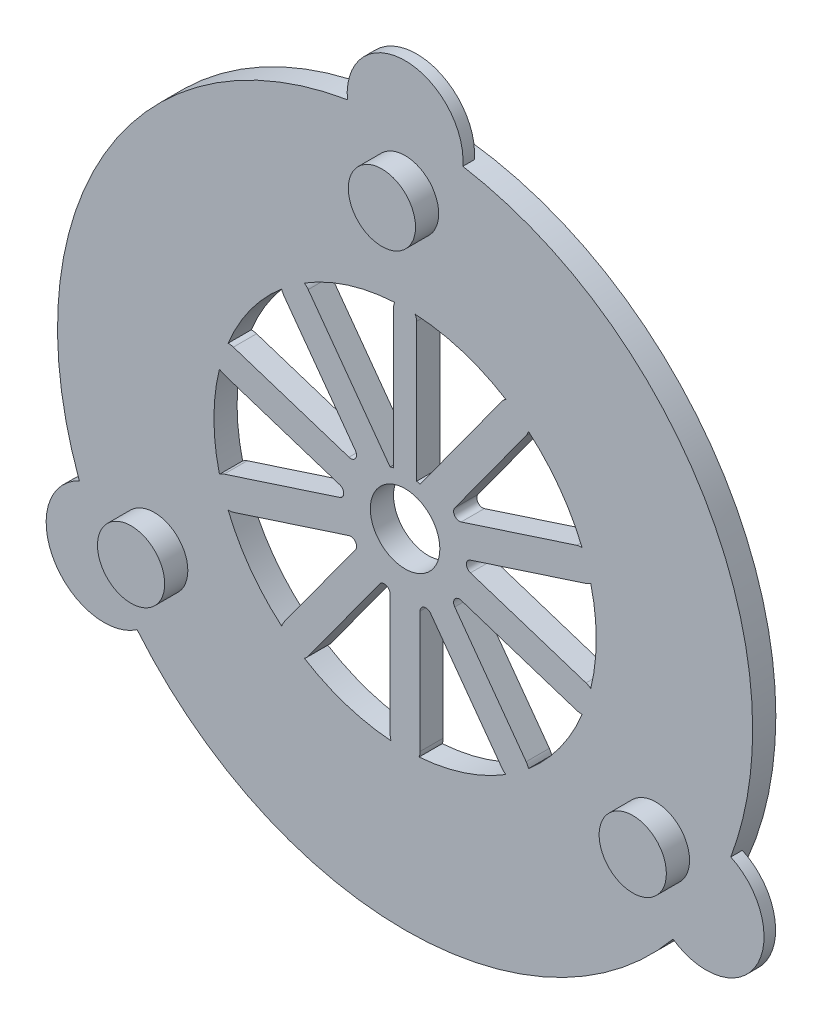
SolidWorks part; units mm, degrees
ref_plane "Спереди" through (0, 0, 0) normal (0, 0, 1) x (1, 0, 0)
ref_plane "Сверху" through (0, 0, 0) normal (0, 1, 0) x (1, 0, 0)
ref_plane "Справа" through (0, 0, 0) normal (1, 0, 0) x (0, 0, -1)
sketch "Sketch1" plane through (0, 0, 0) normal (0, 0, 1) x (1, 0, 0)
  line L0 (3.9, 6.755) -> (7.8, 0) construction
  line L2 (5.85, 10.1325) -> (11.7, 0) construction
  line L4 (7.8, 13.51) -> (15.6, 0) construction
  circle A61 centre (0, 0) radius 20
  circle A131 centre (0, 0) radius 1.25
  circle A484 centre (3.9, 0) radius 1.25
  circle A485 centre (7.8, 0) radius 1.25
  circle A486 centre (11.7, 0) radius 1.25
  circle A487 centre (15.6, 0) radius 1.25
  circle A488 centre (1.95, -3.3775) radius 1.25
  circle A489 centre (3.9, -6.755) radius 1.25
  circle A490 centre (5.85, -10.1325) radius 1.25
  circle A491 centre (7.8, -13.51) radius 1.25
  circle A492 centre (-1.95, -3.3775) radius 1.25
  circle A493 centre (-3.9, -6.755) radius 1.25
  circle A494 centre (-5.85, -10.1325) radius 1.25
  circle A495 centre (-7.8, -13.51) radius 1.25
  circle A496 centre (-3.9, 0) radius 1.25
  circle A497 centre (-7.8, 0) radius 1.25
  circle A498 centre (-11.7, 0) radius 1.25
  circle A499 centre (-15.6, 0) radius 1.25
  circle A500 centre (-1.95, 3.3775) radius 1.25
  circle A501 centre (-3.9, 6.755) radius 1.25
  circle A502 centre (-5.85, 10.1325) radius 1.25
  circle A503 centre (-7.8, 13.51) radius 1.25
  circle A504 centre (1.95, 3.3775) radius 1.25
  circle A505 centre (3.9, 6.755) radius 1.25
  circle A506 centre (5.85, 10.1325) radius 1.25
  circle A507 centre (7.8, 13.51) radius 1.25
  circle A508 centre (5.85, 3.3775) radius 1.25
  circle A509 centre (7.8, 6.755) radius 1.25
  circle A510 centre (9.75, 3.3775) radius 1.25
  circle A511 centre (11.7, 6.755) radius 1.25
  circle A512 centre (9.7491, 10.1341) radius 1.25
  circle A513 centre (13.6509, 3.3759) radius 1.25
  circle A514 centre (5.85, -3.3791) radius 1.25
  circle A515 centre (9.75, -3.3791) radius 1.25
  circle A516 centre (7.8, -6.7566) radius 1.25
  circle A517 centre (11.7, -6.7566) radius 1.25
  circle A518 centre (9.7491, -10.1356) radius 1.25
  circle A519 centre (13.6509, -3.3775) radius 1.25
  circle A520 centre (-0.0013, -6.7573) radius 1.25
  circle A521 centre (1.9487, -10.1348) radius 1.25
  circle A522 centre (-1.9513, -10.1348) radius 1.25
  circle A523 centre (-0.0013, -13.5123) radius 1.25
  circle A524 centre (-3.9032, -13.5123) radius 1.25
  circle A525 centre (3.9005, -13.5123) radius 1.25
  circle A526 centre (-5.8527, -3.3791) radius 1.25
  circle A527 centre (-7.8027, -6.7566) radius 1.25
  circle A528 centre (-9.7527, -3.3791) radius 1.25
  circle A529 centre (-11.7027, -6.7566) radius 1.25
  circle A530 centre (-13.6536, -3.3775) radius 1.25
  circle A531 centre (-9.7518, -10.1356) radius 1.25
  circle A532 centre (-5.8527, 3.3775) radius 1.25
  circle A533 centre (-9.7527, 3.3775) radius 1.25
  circle A534 centre (-7.8027, 6.755) radius 1.25
  circle A535 centre (-11.7027, 6.755) radius 1.25
  circle A536 centre (-9.7518, 10.1341) radius 1.25
  circle A537 centre (-13.6536, 3.3759) radius 1.25
  circle A538 centre (-0.0014, 6.7558) radius 1.25
  circle A539 centre (-1.9514, 10.1333) radius 1.25
  circle A540 centre (1.9486, 10.1333) radius 1.25
  circle A541 centre (-0.0014, 13.5108) radius 1.25
  circle A542 centre (3.9005, 13.5108) radius 1.25
  circle A543 centre (-3.9032, 13.5108) radius 1.25
  circle A544 centre (13.65, -1.1258) radius 2.2517 construction
  circle A545 centre (11.7009, -4.5044) radius 2.2522 construction
  circle A546 centre (9.75, -7.8834) radius 2.2522 construction
  circle A547 centre (7.7987, -11.2591) radius 2.2509 construction
  circle A548 centre (13.65, -1.1258) radius 0.65
  circle A549 centre (11.7009, -4.5044) radius 0.65
  circle A550 centre (9.75, -7.8834) radius 0.65
  circle A551 centre (7.7987, -11.2591) radius 0.65
  circle A552 centre (9.75, -1.1258) radius 0.65
  circle A553 centre (7.8009, -4.5044) radius 0.65
  circle A554 centre (5.85, -7.8834) radius 0.65
  circle A555 centre (3.8987, -11.2591) radius 0.65
  circle A556 centre (5.85, -1.1258) radius 0.65
  circle A557 centre (3.9009, -4.5044) radius 0.65
  circle A558 centre (1.95, -7.8834) radius 0.65
  circle A559 centre (-0.0013, -11.2591) radius 0.65
  circle A560 centre (1.95, -1.1258) radius 0.65
  circle A561 centre (0.0009, -4.5044) radius 0.65
  circle A562 centre (-1.95, -7.8834) radius 0.65
  circle A563 centre (-3.9013, -11.2591) radius 0.65
  circle A564 centre (-1.95, -1.1258) radius 0.65
  circle A565 centre (-3.8991, -4.5044) radius 0.65
  circle A566 centre (-5.85, -7.8834) radius 0.65
  circle A567 centre (-7.8013, -11.2591) radius 0.65
  circle A568 centre (-5.85, -1.1258) radius 0.65
  circle A569 centre (-7.7991, -4.5044) radius 0.65
  circle A570 centre (-9.75, -7.8834) radius 0.65
  circle A572 centre (-9.75, -1.1258) radius 0.65
  circle A573 centre (-11.6991, -4.5044) radius 0.65
  circle A576 centre (-13.65, -1.1258) radius 0.65
  circle A587 centre (0, 2.2517) radius 2.2517 construction
  circle A588 centre (0, 2.2517) radius 0.65
  circle A589 centre (3.9, 2.2517) radius 0.65
  circle A590 centre (7.8, 2.2517) radius 0.65
  circle A591 centre (11.7, 2.2517) radius 0.65
  circle A592 centre (15.6, 2.2517) radius 0.65
  circle A593 centre (1.9491, 5.6297) radius 2.2522 construction
  circle A594 centre (1.9491, 5.6297) radius 0.65
  circle A595 centre (5.8491, 5.6297) radius 0.65
  circle A596 centre (9.7491, 5.6297) radius 0.65
  circle A597 centre (13.6491, 5.6297) radius 0.65
  circle A598 centre (3.8991, 9.0072) radius 2.2522 construction
  circle A599 centre (3.8991, 9.0072) radius 0.65
  circle A600 centre (7.7991, 9.0072) radius 0.65
  circle A601 centre (11.6991, 9.0072) radius 0.65
  circle A602 centre (5.85, 12.3842) radius 2.2517 construction
  circle A603 centre (5.85, 12.3842) radius 0.65
  circle A604 centre (9.75, 12.3842) radius 0.65
  circle A605 centre (5.85, -14.6358) radius 0.65
  circle A606 centre (1.9509, -14.6353) radius 0.65
  circle A607 centre (-1.9491, -14.6353) radius 0.65
  circle A608 centre (-5.85, -14.6358) radius 0.65
  circle A609 centre (-15.6, 2.2517) radius 0.65
  circle A610 centre (-13.65, 5.6281) radius 0.65
  circle A611 centre (-11.7, 9.0056) radius 0.65
  circle A612 centre (-9.75, 12.3842) radius 0.65
  circle A613 centre (-5.85, 12.3842) radius 0.65
  circle A614 centre (-1.95, 12.3842) radius 0.65
  circle A615 centre (1.95, 12.3842) radius 0.65
  circle A616 centre (-7.8, 9.0056) radius 0.65
  circle A617 centre (-9.75, 5.6281) radius 0.65
  circle A618 centre (-11.7, 2.2517) radius 0.65
  circle A619 centre (-3.9, 9.0056) radius 0.65
  circle A620 centre (-5.85, 5.6281) radius 0.65
  circle A621 centre (-7.8, 2.2517) radius 0.65
  circle A622 centre (0, 9.0056) radius 0.65
  circle A623 centre (-1.95, 5.6281) radius 0.65
  circle A624 centre (-3.9, 2.2517) radius 0.65
  circle A625 centre (-15.5991, -4.5044) radius 0.65
  circle A626 centre (-13.65, -7.8834) radius 0.65
  circle A627 centre (-17.55, -7.8834) radius 0.65
  circle A628 centre (-19.5013, -11.2591) radius 0.65
  circle A629 centre (-15.6013, -11.2591) radius 0.65
  circle A630 centre (-11.7013, -11.2591) radius 0.65
  point P51 (0, 0)
  point P125 (-0.0013, -0.0008)
  point P231 (0, 0)
  dimension "D1" = 5
  dimension "D3" = 6
  dimension "D5" = 8
  dimension "D7" = 4
  dimension "D11" = 4
  dimension "D2" = 6
  dimension "D6" = 5
  dimension "D8" = 3
  dimension "D9" = 2
  dimension "D4" = 1.3
  dimension "D10" = 3
ref_plane "Plane1" through (0, 0, 10) normal (0, 0, 1) x (1, 0, 0)
sketch "Sketch2" plane through (0, 0, 10) normal (0, 0, 1) x (1, 0, 0)
  line L0 (-0.0032, 16) -> (0, 0) construction
  line L1 (0.9968, 16.0002) -> (1, 0.0002)
  line L2 (-1.0032, 15.9998) -> (-1, -0.0002)
  line L3 (8.3575, 13.7047) -> (-1.0445, 0.7585)
  line L4 (10.4465, 12.1876) -> (1.0445, -0.7585)
  line L5 (9.402, 12.9462) -> (0, 0) construction
  line L6 (14.8168, 6.1749) -> (-0.3991, 1.2276)
  line L7 (15.6151, 3.7197) -> (0.3991, -1.2276)
  line L8 (15.2159, 4.9473) -> (0, 0) construction
  line L9 (15.6165, -3.7135) -> (0.3987, 1.2278)
  line L10 (14.8192, -6.169) -> (-0.3987, -1.2278)
  line L11 (15.2179, -4.9412) -> (0, 0) construction
  line L12 (10.4513, -12.1834) -> (1.0442, 0.759)
  line L13 (8.363, -13.7014) -> (-1.0442, -0.759)
  line L14 (9.4072, -12.9424) -> (0, 0) construction
  line L15 (1.2941, -15.9997) -> (1.2909, 0.0003)
  line L16 (-1.2877, -16.0003) -> (-1.2909, -0.0003)
  line L17 (0.0032, -16) -> (0, 0) construction
  line L18 (-8.3575, -13.7047) -> (1.0445, -0.7585)
  line L19 (-10.4465, -12.1876) -> (-1.0445, 0.7585)
  line L20 (-9.402, -12.9462) -> (0, 0) construction
  line L21 (-14.8168, -6.1749) -> (0.3991, -1.2276)
  line L22 (-15.6151, -3.7197) -> (-0.3991, 1.2276)
  line L23 (-15.2159, -4.9473) -> (0, 0) construction
  line L24 (-15.6165, 3.7135) -> (-0.3987, -1.2278)
  line L25 (-14.8192, 6.169) -> (0.3987, 1.2278)
  line L26 (-15.2179, 4.9412) -> (0, 0) construction
  line L27 (-10.4513, 12.1834) -> (-1.0442, -0.759)
  line L28 (-8.363, 13.7014) -> (1.0442, 0.759)
  line L29 (-9.4072, 12.9424) -> (0, 0) construction
  circle A52 centre (0, 0) radius 16.85 construction
  circle A53 centre (0, 0) radius 18.85
  arc A54 (0.9968, 16.0002) -> (-1.0032, 15.9998) centre (-0.0032, 16) ccw
  arc A55 (-1, -0.0002) -> (1, 0.0002) centre (0, 0) ccw
  arc A56 (10.4465, 12.1876) -> (8.3575, 13.7047) centre (9.402, 12.9462) ccw
  arc A57 (-1.0445, 0.7585) -> (1.0445, -0.7585) centre (0, 0) ccw
  arc A58 (15.6151, 3.7197) -> (14.8168, 6.1749) centre (15.2159, 4.9473) ccw
  arc A59 (-0.3991, 1.2276) -> (0.3991, -1.2276) centre (0, 0) ccw
  arc A60 (14.8192, -6.169) -> (15.6165, -3.7135) centre (15.2179, -4.9412) ccw
  arc A61 (0.3987, 1.2278) -> (-0.3987, -1.2278) centre (0, 0) ccw
  arc A62 (8.363, -13.7014) -> (10.4513, -12.1834) centre (9.4072, -12.9424) ccw
  arc A63 (1.0442, 0.759) -> (-1.0442, -0.759) centre (0, 0) ccw
  arc A64 (-1.2877, -16.0003) -> (1.2941, -15.9997) centre (0.0032, -16) ccw
  arc A65 (1.2909, 0.0003) -> (-1.2909, -0.0003) centre (0, 0) ccw
  arc A66 (-10.4465, -12.1876) -> (-8.3575, -13.7047) centre (-9.402, -12.9462) ccw
  arc A67 (1.0445, -0.7585) -> (-1.0445, 0.7585) centre (0, 0) ccw
  arc A68 (-15.6151, -3.7197) -> (-14.8168, -6.1749) centre (-15.2159, -4.9473) ccw
  arc A69 (0.3991, -1.2276) -> (-0.3991, 1.2276) centre (0, 0) ccw
  arc A70 (-14.8192, 6.169) -> (-15.6165, 3.7135) centre (-15.2179, 4.9412) ccw
  arc A71 (-0.3987, -1.2278) -> (0.3987, 1.2278) centre (0, 0) ccw
  arc A72 (-8.363, 13.7014) -> (-10.4513, 12.1834) centre (-9.4072, 12.9424) ccw
  arc A73 (-1.0442, -0.759) -> (1.0442, 0.759) centre (0, 0) ccw
  point P1 (-0.0016, 8)
  point P9 (4.701, 6.4731)
  point P15 (7.608, 2.4737)
  point P21 (7.6089, -2.4706)
  point P27 (4.7036, -6.4712)
  point P33 (0.0016, -8)
  point P39 (-4.701, -6.4731)
  point P45 (-7.608, -2.4737)
  point P51 (-7.6089, 2.4706)
  point P57 (-4.7036, 6.4712)
  point P62 (0, 0)
  dimension "D1" = 2
extrude "Boss-Extrude1" add sketch "Sketch2" along normal blind 2 contours L4 A56 L3 L1 L6 | L1 A54 L2 L28 L3 | L28 A72 L27 L25 L2 | L25 A70 L24 L22 L27 | L22 A68 L21 L19 L24 | L19 A66 L18 L16 L21 | L16 A64 L15 L13 L18 | L13 A62 L12 L10 L15 | L10 A60 L9 L7 L12 | L7 A58 L6 L4 L9
sketch "Sketch3" plane through (0, 0, 12) normal (0, 0, 1) x (1, 0, 0)
  circle A0 centre (0, 0) radius 16.5
  circle A1 centre (0, 0) radius 30
extrude "Boss-Extrude2" add sketch "Sketch3" against normal blind 2
sketch "Sketch4" plane through (0, 0, 12) normal (0, 0, 1) x (1, 0, 0)
  circle A0 centre (0, 0) radius 25 construction
  circle A1 centre (0, 25) radius 2.9
  circle A2 centre (21.6506, -12.5) radius 2.9
  circle A3 centre (-21.6506, -12.5) radius 2.9
  point P11 (0, 0)
  dimension "D1" = 3
extrude "Boss-Extrude3" add sketch "Sketch4" along normal blind 2
sketch "Sketch6" plane through (0, 0, 11) normal (0, 0, -1) x (-1, 0, 0)
  circle A0 centre (0, 30) radius 5
  circle A2 centre (25.9808, -15) radius 5
  circle A3 centre (-25.9808, -15) radius 5
  point P10 (0, 0)
  dimension "D1" = 3
extrude "Boss-Extrude4" add sketch "Sketch6" against normal blind 1
sketch "Sketch5" plane through (0, 0, 10) normal (0, 0, -1) x (-1, 0, 0)
  circle A0 centre (0, 25) radius 3
  circle A1 centre (21.6506, -12.5) radius 3
  circle A2 centre (-21.6506, -12.5) radius 3
sketch "Sketch9" plane through (0, 0, 0) normal (0, 0, 1) x (1, 0, 0)
  line L0 (-7.8, 13.51) -> (-7.8027, 6.755) construction
  line L1 (-9.7518, 10.1341) -> (-5.85, 10.1325) construction
  line L2 (-7.8008, 11.6325) -> (-7.8019, 8.6325) construction
  line L3 (-6.8008, 11.6321) -> (-6.8019, 8.6321)
  line L4 (-8.8008, 11.6329) -> (-8.8019, 8.6329)
  line L5 (-4.9008, 11.6329) -> (-4.9019, 8.6329)
  line L6 (-2.9008, 11.6321) -> (-2.9019, 8.6321)
  line L7 (-3.9008, 11.6325) -> (-3.9019, 8.6325) construction
  line L8 (-1.0008, 11.6329) -> (-1.0019, 8.6329)
  line L9 (0.9992, 11.6321) -> (0.9981, 8.6321)
  line L10 (-0.0008, 11.6325) -> (-0.0019, 8.6325) construction
  line L11 (2.8992, 11.6329) -> (2.8981, 8.6329)
  line L12 (4.8992, 11.6321) -> (4.8981, 8.6321)
  line L13 (3.8992, 11.6325) -> (3.8981, 8.6325) construction
  line L14 (6.7992, 11.6329) -> (6.7981, 8.6329)
  line L15 (8.7992, 11.6321) -> (8.7981, 8.6321)
  line L16 (7.7992, 11.6325) -> (7.7981, 8.6325) construction
  line L17 (-9.7518, 10.1341) -> (-9.7527, 3.3775) construction
  line L18 (-11.7027, 6.755) -> (-7.8027, 6.755) construction
  line L19 (-10.7035, 1.877) -> (-10.702, 4.877)
  line L22 (-9.7527, 3.3775) -> (-5.8527, 3.3775) construction
  line L25 (-7.8027, 6.755) -> (-7.8, 0) construction
  line L26 (-7.8035, 1.8775) -> (-7.8019, 4.8775) construction
  line L27 (-8.8035, 1.878) -> (-8.8019, 4.878)
  line L28 (-6.8035, 1.877) -> (-6.8019, 4.877)
  line L29 (-2.9035, 1.877) -> (-2.9019, 4.877)
  line L30 (-4.9035, 1.878) -> (-4.9019, 4.878)
  line L31 (-3.9035, 1.8775) -> (-3.9019, 4.8775) construction
  line L32 (0.9965, 1.877) -> (0.9981, 4.877)
  line L33 (-1.0035, 1.878) -> (-1.0019, 4.878)
  line L34 (-0.0035, 1.8775) -> (-0.0019, 4.8775) construction
  line L35 (4.8965, 1.877) -> (4.8981, 4.877)
  line L36 (2.8965, 1.878) -> (2.8981, 4.878)
  line L37 (3.8965, 1.8775) -> (3.8981, 4.8775) construction
  line L38 (8.7965, 1.877) -> (8.7981, 4.877)
  line L39 (6.7965, 1.878) -> (6.7981, 4.878)
  line L40 (7.7965, 1.8775) -> (7.7981, 4.8775) construction
  line L41 (12.6965, 1.877) -> (12.6981, 4.877)
  line L42 (10.6965, 1.878) -> (10.6981, 4.878)
  line L43 (11.6965, 1.8775) -> (11.6981, 4.8775) construction
  line L44 (-12.7035, 1.878) -> (-12.7019, 4.878)
  line L45 (-11.7035, 1.8775) -> (-11.702, 4.8775) construction
  line L46 (-9.7527, -3.3791) -> (-5.8527, -3.3791) construction
  line L47 (-7.8, 0) -> (-7.8027, -6.7566) construction
  line L48 (-7.8046, -4.8791) -> (-7.8008, -1.8791) construction
  line L49 (-8.8046, -4.8778) -> (-8.8008, -1.8778)
  line L50 (-6.8046, -4.8804) -> (-6.8008, -1.8804)
  line L51 (-2.9046, -4.8804) -> (-2.9008, -1.8804)
  line L52 (-4.9046, -4.8778) -> (-4.9008, -1.8778)
  line L53 (-3.9046, -4.8791) -> (-3.9008, -1.8791) construction
  line L54 (0.9954, -4.8804) -> (0.9992, -1.8804)
  line L55 (-1.0046, -4.8778) -> (-1.0008, -1.8778)
  line L56 (-0.0046, -4.8791) -> (-0.0008, -1.8791) construction
  line L57 (4.8954, -4.8804) -> (4.8992, -1.8804)
  line L58 (2.8954, -4.8778) -> (2.8992, -1.8778)
  line L59 (3.8954, -4.8791) -> (3.8992, -1.8791) construction
  line L60 (8.7954, -4.8804) -> (8.7992, -1.8804)
  line L61 (6.7954, -4.8778) -> (6.7992, -1.8778)
  line L62 (7.7954, -4.8791) -> (7.7992, -1.8791) construction
  line L63 (12.6954, -4.8804) -> (12.6992, -1.8804)
  line L64 (10.6954, -4.8778) -> (10.6992, -1.8778)
  line L65 (11.6954, -4.8791) -> (11.6992, -1.8791) construction
  line L66 (-10.7046, -4.8804) -> (-10.7008, -1.8804)
  line L67 (-12.7046, -4.8778) -> (-12.7008, -1.8778)
  line L68 (-11.7046, -4.8791) -> (-11.7008, -1.8791) construction
  line L69 (-9.7518, -10.1356) -> (-5.482, -10.1356) construction
  line L70 (-7.8027, -6.7566) -> (-7.8, -13.51) construction
  line L71 (-7.8007, -8.6356) -> (-7.8007, -11.6356) construction
  line L72 (-6.8007, -8.6356) -> (-6.8007, -11.6356)
  line L73 (-8.8007, -8.6356) -> (-8.8007, -11.6356)
  line L74 (-4.9007, -8.6356) -> (-4.9007, -11.6356)
  line L75 (-2.9007, -8.6356) -> (-2.9007, -11.6356)
  line L76 (-3.9007, -8.6356) -> (-3.9007, -11.6356) construction
  line L77 (-1.0007, -8.6356) -> (-1.0007, -11.6356)
  line L78 (0.9993, -8.6356) -> (0.9993, -11.6356)
  line L79 (-0.0007, -8.6356) -> (-0.0007, -11.6356) construction
  line L80 (2.8993, -8.6356) -> (2.8993, -11.6356)
  line L81 (4.8993, -8.6356) -> (4.8993, -11.6356)
  line L82 (3.8993, -8.6356) -> (3.8993, -11.6356) construction
  line L83 (6.7993, -8.6356) -> (6.7993, -11.6356)
  line L84 (8.7993, -8.6356) -> (8.7993, -11.6356)
  line L85 (7.7993, -8.6356) -> (7.7993, -11.6356) construction
  arc A0 (-6.8008, 11.6321) -> (-8.8008, 11.6329) centre (-7.8008, 11.6325) ccw
  arc A1 (-8.8019, 8.6329) -> (-6.8019, 8.6321) centre (-7.8019, 8.6325) ccw
  arc A2 (-2.9008, 11.6321) -> (-4.9008, 11.6329) centre (-3.9008, 11.6325) ccw
  arc A3 (-4.9019, 8.6329) -> (-2.9019, 8.6321) centre (-3.9019, 8.6325) ccw
  arc A4 (0.9992, 11.6321) -> (-1.0008, 11.6329) centre (-0.0008, 11.6325) ccw
  arc A5 (-1.0019, 8.6329) -> (0.9981, 8.6321) centre (-0.0019, 8.6325) ccw
  arc A6 (4.8992, 11.6321) -> (2.8992, 11.6329) centre (3.8992, 11.6325) ccw
  arc A7 (2.8981, 8.6329) -> (4.8981, 8.6321) centre (3.8981, 8.6325) ccw
  arc A8 (8.7992, 11.6321) -> (6.7992, 11.6329) centre (7.7992, 11.6325) ccw
  arc A9 (6.7981, 8.6329) -> (8.7981, 8.6321) centre (7.7981, 8.6325) ccw
  arc A14 (-8.8035, 1.878) -> (-6.8035, 1.877) centre (-7.8035, 1.8775) ccw
  arc A15 (-6.8019, 4.877) -> (-8.8019, 4.878) centre (-7.8019, 4.8775) ccw
  arc A16 (-4.9035, 1.878) -> (-2.9035, 1.877) centre (-3.9035, 1.8775) ccw
  arc A17 (-2.9019, 4.877) -> (-4.9019, 4.878) centre (-3.9019, 4.8775) ccw
  arc A18 (-1.0035, 1.878) -> (0.9965, 1.877) centre (-0.0035, 1.8775) ccw
  arc A19 (0.9981, 4.877) -> (-1.0019, 4.878) centre (-0.0019, 4.8775) ccw
  arc A20 (2.8965, 1.878) -> (4.8965, 1.877) centre (3.8965, 1.8775) ccw
  arc A21 (4.8981, 4.877) -> (2.8981, 4.878) centre (3.8981, 4.8775) ccw
  arc A22 (6.7965, 1.878) -> (8.7965, 1.877) centre (7.7965, 1.8775) ccw
  arc A23 (8.7981, 4.877) -> (6.7981, 4.878) centre (7.7981, 4.8775) ccw
  arc A24 (10.6965, 1.878) -> (12.6965, 1.877) centre (11.6965, 1.8775) ccw
  arc A25 (12.6981, 4.877) -> (10.6981, 4.878) centre (11.6981, 4.8775) ccw
  arc A26 (-12.7035, 1.878) -> (-10.7035, 1.877) centre (-11.7035, 1.8775) ccw
  arc A27 (-10.702, 4.877) -> (-12.7019, 4.878) centre (-11.702, 4.8775) ccw
  arc A28 (-8.8046, -4.8778) -> (-6.8046, -4.8804) centre (-7.8046, -4.8791) ccw
  arc A29 (-6.8008, -1.8804) -> (-8.8008, -1.8778) centre (-7.8008, -1.8791) ccw
  arc A30 (-4.9046, -4.8778) -> (-2.9046, -4.8804) centre (-3.9046, -4.8791) ccw
  arc A31 (-2.9008, -1.8804) -> (-4.9008, -1.8778) centre (-3.9008, -1.8791) ccw
  arc A32 (-1.0046, -4.8778) -> (0.9954, -4.8804) centre (-0.0046, -4.8791) ccw
  arc A33 (0.9992, -1.8804) -> (-1.0008, -1.8778) centre (-0.0008, -1.8791) ccw
  arc A34 (2.8954, -4.8778) -> (4.8954, -4.8804) centre (3.8954, -4.8791) ccw
  arc A35 (4.8992, -1.8804) -> (2.8992, -1.8778) centre (3.8992, -1.8791) ccw
  arc A36 (6.7954, -4.8778) -> (8.7954, -4.8804) centre (7.7954, -4.8791) ccw
  arc A37 (8.7992, -1.8804) -> (6.7992, -1.8778) centre (7.7992, -1.8791) ccw
  arc A38 (10.6954, -4.8778) -> (12.6954, -4.8804) centre (11.6954, -4.8791) ccw
  arc A39 (12.6992, -1.8804) -> (10.6992, -1.8778) centre (11.6992, -1.8791) ccw
  arc A40 (-12.7046, -4.8778) -> (-10.7046, -4.8804) centre (-11.7046, -4.8791) ccw
  arc A41 (-10.7008, -1.8804) -> (-12.7008, -1.8778) centre (-11.7008, -1.8791) ccw
  arc A42 (-6.8007, -8.6356) -> (-8.8007, -8.6356) centre (-7.8007, -8.6356) ccw
  arc A43 (-8.8007, -11.6356) -> (-6.8007, -11.6356) centre (-7.8007, -11.6356) ccw
  arc A44 (-2.9007, -8.6356) -> (-4.9007, -8.6356) centre (-3.9007, -8.6356) ccw
  arc A45 (-4.9007, -11.6356) -> (-2.9007, -11.6356) centre (-3.9007, -11.6356) ccw
  arc A46 (0.9993, -8.6356) -> (-1.0007, -8.6356) centre (-0.0007, -8.6356) ccw
  arc A47 (-1.0007, -11.6356) -> (0.9993, -11.6356) centre (-0.0007, -11.6356) ccw
  arc A48 (4.8993, -8.6356) -> (2.8993, -8.6356) centre (3.8993, -8.6356) ccw
  arc A49 (2.8993, -11.6356) -> (4.8993, -11.6356) centre (3.8993, -11.6356) ccw
  arc A50 (8.7993, -8.6356) -> (6.7993, -8.6356) centre (7.7993, -8.6356) ccw
  arc A51 (6.7993, -11.6356) -> (8.7993, -11.6356) centre (7.7993, -11.6356) ccw
  circle A52 centre (0, 0) radius 16.85 construction
  circle A53 centre (0, 0) radius 18.85
  point P10 (-7.8014, 10.1325)
  point P18 (-3.9014, 10.1325)
  point P25 (-0.0014, 10.1325)
  point P32 (3.8986, 10.1325)
  point P39 (7.7986, 10.1325)
  point P50 (-11.7027, 3.3775)
  point P58 (-7.8027, 3.3775)
  point P68 (-3.9027, 3.3775)
  point P75 (-0.0027, 3.3775)
  point P82 (3.8973, 3.3775)
  point P89 (7.7973, 3.3775)
  point P96 (11.6973, 3.3775)
  point P108 (-7.8027, -3.3791)
  point P116 (-3.9027, -3.3791)
  point P123 (-0.0027, -3.3791)
  point P130 (3.8973, -3.3791)
  point P137 (7.7973, -3.3791)
  point P144 (11.6973, -3.3791)
  point P151 (-11.7027, -3.3791)
  point P162 (-7.8007, -10.1356)
  point P170 (-3.9007, -10.1356)
  point P177 (-0.0007, -10.1356)
  point P184 (3.8993, -10.1356)
  point P191 (7.7993, -10.1356)
  dimension "D1" = 2
  dimension "D15" = 2
  dimension "D2" = 3
  dimension "D4" = 2
  dimension "D5" = 3
  dimension "D6" = 2
  dimension "D7" = 3
  dimension "D9" = 2
  dimension "D12" = 3
  dimension "D13" = 2
  dimension "D3" = 5
  dimension "D8" = 6
  dimension "D10" = 6
  dimension "D11" = 2
  dimension "D14" = 5
sketch "Sketch10" plane through (0, 0, 20) normal (0, 0, 1) x (1, 0, 0)
  line L1 (-9.8683, 13.2069) -> (9.8683, 13.2069)
  line L2 (-9.8683, 13.2069) -> (-9.8683, -13.2069)
  line L3 (-9.8683, -13.2069) -> (9.8683, -13.2069)
  line L4 (9.8683, 13.2069) -> (9.8683, -13.2069)
  line L5 (-9.8683, 13.2069) -> (9.8683, -13.2069) construction
  line L6 (-9.8683, -13.2069) -> (9.8683, 13.2069) construction
  line L7 (-14.0535, 6.7065) -> (14.0535, 6.7065)
  line L8 (-14.0535, 6.7065) -> (-14.0535, -6.7065)
  line L9 (-14.0535, -6.7065) -> (14.0535, -6.7065)
  line L10 (14.0535, 6.7065) -> (14.0535, -6.7065)
  line L11 (-14.0535, 6.7065) -> (14.0535, -6.7065) construction
  line L12 (-14.0535, -6.7065) -> (14.0535, 6.7065) construction
  circle A0 centre (0, 0) radius 21.6778
  point P0 (0, 0)
  point P6 (0, 0)
fillet "Fillet1" [suppressed] radius 0.5
sketch "Sketch12" plane through (0, 0, 10) normal (0, 0, -1) x (-1, 0, 0)
  line L0 (-1.9972, -6.0904) -> (1.9972, 6.0904) construction
  line L3 (-2.4723, -5.9346) -> (1.5221, 6.2462)
  line L4 (-1.5221, -6.2462) -> (2.4723, 5.9346)
  line L5 (-6.4109, -0.4826) -> (6.4082, -0.5174)
  line L6 (-6.4082, 0.5174) -> (6.4109, 0.4826)
  line L7 (-6.4095, 0.0174) -> (6.4095, -0.0174) construction
  line L8 (-2.44, 5.948) -> (1.4881, -6.2544)
  line L9 (-1.4881, 6.2544) -> (2.44, -5.948)
  line L10 (-1.9641, 6.1012) -> (1.9641, -6.1012) construction
  line L11 (4.9029, 4.1586) -> (-5.4885, -3.348)
  line L12 (5.4885, 3.348) -> (-4.9029, -4.1586)
  line L13 (5.1957, 3.7533) -> (-5.1957, -3.7533) construction
  line L14 (5.4702, -3.3778) -> (-4.8802, 4.1852)
  line L15 (4.8802, -4.1852) -> (-5.4702, 3.3778)
  line L16 (5.1752, -3.7815) -> (-5.1752, 3.7815) construction
  circle A2 centre (0, 0) radius 3
  arc A3 (-2.4723, -5.9346) -> (-1.5221, -6.2462) centre (-1.9972, -6.0904) ccw
  arc A4 (2.4723, 5.9346) -> (1.5221, 6.2462) centre (1.9972, 6.0904) ccw
  arc A5 (-6.4082, 0.5174) -> (-6.4109, -0.4826) centre (-6.4095, 0.0174) ccw
  arc A6 (6.4082, -0.5174) -> (6.4109, 0.4826) centre (6.4095, -0.0174) ccw
  arc A7 (-1.4881, 6.2544) -> (-2.44, 5.948) centre (-1.9641, 6.1012) ccw
  arc A8 (1.4881, -6.2544) -> (2.44, -5.948) centre (1.9641, -6.1012) ccw
  arc A9 (5.4885, 3.348) -> (4.9029, 4.1586) centre (5.1957, 3.7533) ccw
  arc A10 (-5.4885, -3.348) -> (-4.9029, -4.1586) centre (-5.1957, -3.7533) ccw
  arc A11 (4.8802, -4.1852) -> (5.4702, -3.3778) centre (5.1752, -3.7815) ccw
  arc A12 (-4.8802, 4.1852) -> (-5.4702, 3.3778) centre (-5.1752, 3.7815) ccw
  point P5 (0, 0)
  point P15 (0, 0)
  point P22 (0, 0)
  point P29 (0, 0)
  point P36 (0, 0)
  point P41 (0, 0)
  dimension "D1" = 1
extrude "Boss-Extrude5" [suppressed] add sketch "Sketch12" against normal blind 2
sketch "Sketch13" plane through (0, 0, 10) normal (0, 0, -1) x (-1, 0, 0)
  circle A0 centre (0, 0) radius 4.1773
extrude "Boss-Extrude6" add sketch "Sketch13" against normal blind 2
fillet "Fillet2" radius 0.5 8 edges at (-3.38, 2.4547, 11) (-4.1773, -0.0008, 11) (-3.379, -2.456, 11) (-1.2901, -3.9731, 11) (1.2917, -3.9726, 11) (3.38, -2.4547, 11) (4.1773, 0.0008, 11) (3.379, 2.456, 11)
sketch "Sketch14" plane through (0, 0, 10) normal (0, 0, -1) x (-1, 0, 0)
  circle A0 centre (0, 0) radius 3
extrude "Cut-Extrude1" cut sketch "Sketch14" against normal blind 20
